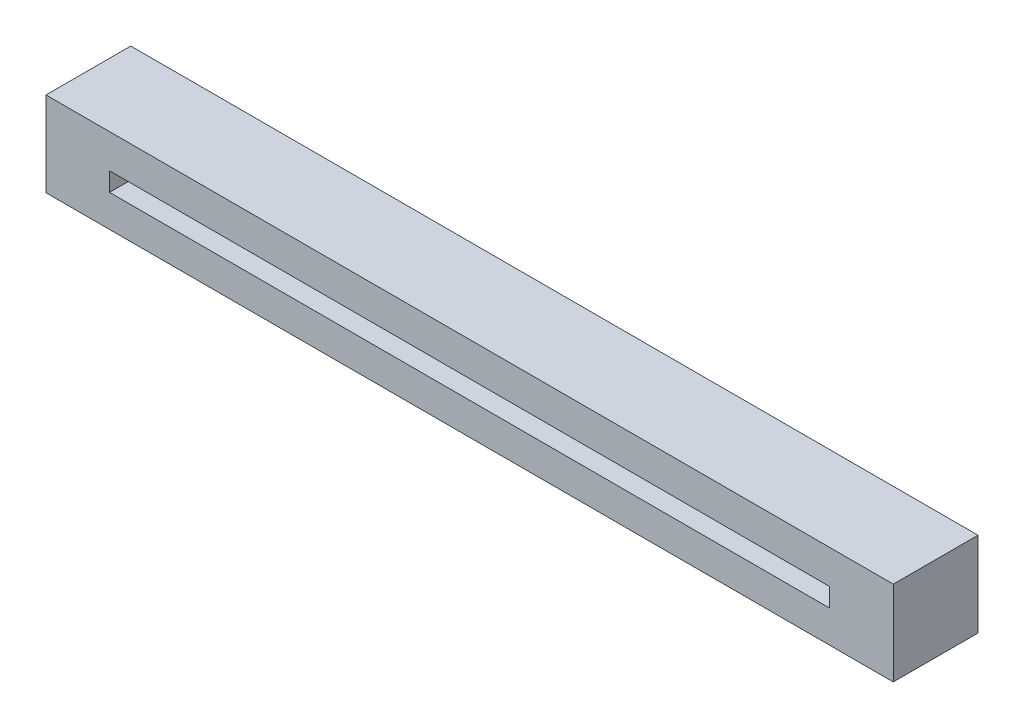
SolidWorks part; units mm, degrees
ref_plane "前视基准面" through (0, 0, 0) normal (0, 0, 1) x (1, 0, 0)
ref_plane "上视基准面" through (0, 0, 0) normal (0, 1, 0) x (1, 0, 0)
ref_plane "右视基准面" through (0, 0, 0) normal (1, 0, 0) x (0, 0, -1)
sketch "草图1" plane through (0, 0, 0) normal (0, 0, 1) x (1, 0, 0)
  line L1 (-46.8276, -22.3448) -> (73.1724, -22.3448)
  line L2 (-46.8276, -22.3448) -> (-46.8276, -34.3448)
  line L3 (-46.8276, -34.3448) -> (73.1724, -34.3448)
  line L4 (73.1724, -22.3448) -> (73.1724, -34.3448)
  dimension "D1" = 120
  dimension "D2" = 12
extrude "凸台-拉伸2" add sketch "草图1" along normal blind 12
sketch "草图4" plane through (0, 0, 12) normal (0, 0, 1) x (1, 0, 0)
  line L1 (-37.8276, -27.1448) -> (64.1724, -27.1448)
  line L2 (-37.8276, -27.1448) -> (-37.8276, -29.7949)
  line L3 (-37.8276, -29.7949) -> (64.1724, -29.7949)
  line L4 (64.1724, -27.1448) -> (64.1724, -29.7949)
extrude "切除-拉伸2" cut sketch "草图4" against normal blind 8
